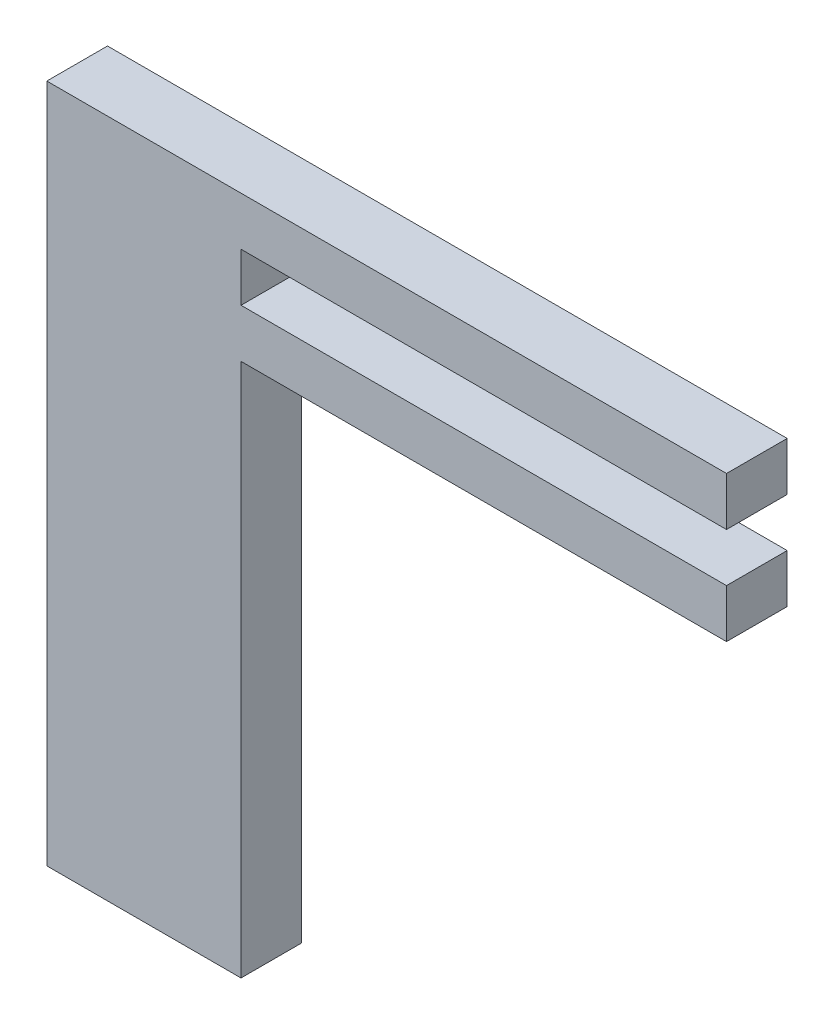
SolidWorks part; units mm, degrees
ref_plane "Plano frontal" through (0, 0, 0) normal (0, 0, 1) x (1, 0, 0)
ref_plane "Plano superior" through (0, 0, 0) normal (0, 1, 0) x (1, 0, 0)
ref_plane "Plano direito" through (0, 0, 0) normal (1, 0, 0) x (0, 0, -1)
sketch "Esboço2" plane through (0, 0, 0) normal (0, 0, 1) x (1, 0, 0)
  line L1 (-4, 14) -> (4, 14)
  line L2 (-4, 14) -> (-4, -14)
  line L3 (-4, -14) -> (4, -14)
  line L4 (4, 14) -> (4, -14)
  line L5 (-4, 14) -> (4, -14) construction
  line L6 (-4, -14) -> (4, 14) construction
  point P0 (0, 0)
  dimension "D1" = 28
  dimension "D2" = 8
extrude "Ressalto-extrusão1" add sketch "Esboço2" along normal blind 2.5
sketch "Esboço3" plane through (0, -14, 0) normal (0, -1, 0) x (1, 0, 0)
  line L0 (0, 0) -> (0, 2.5) construction
  line L1 (-4, 0) -> (4, 0) construction
  line L2 (-4, 2.5) -> (4, 2.5) construction
  line L4 (-1.5, 1.55) -> (1.5, 1.55)
  line L5 (-1.5, 1.55) -> (-1.5, 0.95)
  line L6 (-1.5, 0.95) -> (1.5, 0.95)
  line L7 (1.5, 1.55) -> (1.5, 0.95)
  line L8 (-1.5, 1.55) -> (1.5, 0.95) construction
  line L9 (-1.5, 0.95) -> (1.5, 1.55) construction
  point P6 (0, 1.25)
  dimension "D1" = 0.6
  dimension "D2" = 3
extrude "Corte-extrusão1" cut sketch "Esboço3" against normal blind 25
sketch "Esboço4" plane through (4, 0, 0) normal (1, 0, 0) x (0, 0, -1)
  line L0 (0, -14) -> (0, 14) construction
  line L1 (-2.5, 14) -> (0, 14)
  line L2 (-2.5, 14) -> (-2.5, 12)
  line L3 (-2.5, 12) -> (0, 12)
  line L4 (0, 14) -> (0, 12)
  line L5 (-2.5, -14) -> (-2.5, 14) construction
  line L6 (-2.5, 10) -> (0, 10)
  line L7 (-2.5, 10) -> (-2.5, 8)
  line L8 (-2.5, 8) -> (0, 8)
  line L9 (0, 10) -> (0, 8)
  dimension "D1" = 2
  dimension "D2" = 2
  dimension "D3" = 2
extrude "Ressalto-extrusão2" add sketch "Esboço4" along normal blind 20
